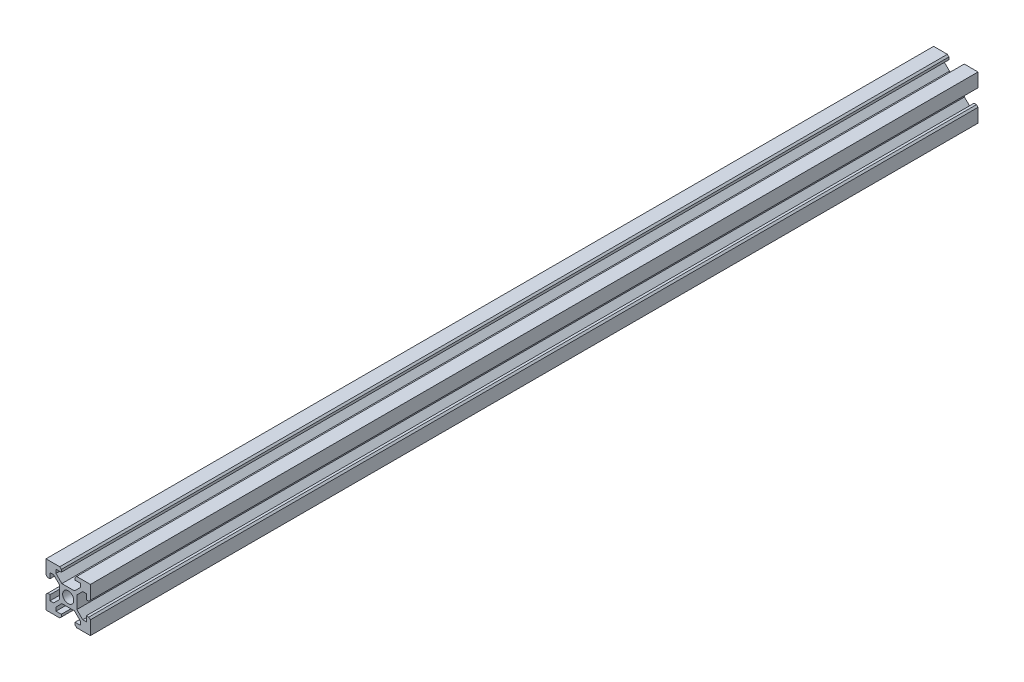
SolidWorks part; units mm, degrees
material "Cast Alloy Steel"
ref_plane "Front Plane" through (0, 0, 0) normal (0, 0, 1) x (1, 0, 0)
ref_plane "Top Plane" through (0, 0, 0) normal (0, 1, 0) x (1, 0, 0)
ref_plane "Right Plane" through (0, 0, 0) normal (1, 0, 0) x (0, 0, -1)
sketch "Sketch1" plane through (0, 0, 0) normal (0, 0, 1) x (1, 0, 0)
  line L0 (3.9, -2.8393) -> (6.5607, -5.5)
  line L1 (-10, 10) -> (10, 10) construction
  line L2 (-10, 10) -> (-10, -10) construction
  line L3 (-10, -10) -> (10, -10) construction
  line L4 (10, 10) -> (10, -10) construction
  line L5 (-10, 10) -> (10, -10) construction
  line L6 (-10, -10) -> (10, 10) construction
  line L7 (-3.9, -3.9) -> (3.9, -3.9) construction
  line L8 (-3.9, -3.9) -> (-3.9, 3.9) construction
  line L9 (-3.9, 3.9) -> (3.9, 3.9) construction
  line L10 (3.9, -3.9) -> (3.9, 3.9) construction
  line L11 (-3.9, -3.9) -> (3.9, 3.9) construction
  line L12 (-3.9, 3.9) -> (3.9, -3.9) construction
  line L13 (-10, 10) -> (-5.5, 10) construction
  line L14 (-10, 10) -> (-10, 5.5) construction
  line L15 (-10, 5.5) -> (-5.5, 5.5) construction
  line L16 (-5.5, 10) -> (-5.5, 5.5) construction
  line L17 (10, 10) -> (5.5, 10) construction
  line L18 (10, 10) -> (10, 5.5) construction
  line L19 (10, 5.5) -> (5.5, 5.5) construction
  line L20 (5.5, 10) -> (5.5, 5.5) construction
  line L21 (-10, -10) -> (-5.5, -10) construction
  line L22 (-10, -10) -> (-10, -5.5) construction
  line L23 (-10, -5.5) -> (-5.5, -5.5) construction
  line L24 (-5.5, -10) -> (-5.5, -5.5) construction
  line L25 (10, -10) -> (5.5, -10) construction
  line L26 (10, -10) -> (10, -5.5) construction
  line L27 (10, -5.5) -> (5.5, -5.5) construction
  line L28 (5.5, -10) -> (5.5, -5.5) construction
  line L29 (2.8393, -3.9) -> (5.5, -6.5607)
  line L30 (-5.5, 6.5607) -> (-2.8393, 3.9)
  line L31 (-6.5607, 5.5) -> (-3.9, 2.8393)
  line L32 (5.5, 6.5607) -> (2.8393, 3.9)
  line L33 (6.5607, 5.5) -> (3.9, 2.8393)
  line L34 (-6.5607, -5.5) -> (-3.9, -2.8393)
  line L35 (-5.5, -6.5607) -> (-2.8393, -3.9)
  line L36 (-2.8393, 3.9) -> (2.8393, 3.9)
  line L37 (-3.9, 2.8393) -> (-3.9, -2.8393)
  line L38 (-2.8393, -3.9) -> (2.8393, -3.9)
  line L39 (3.9, -2.8393) -> (3.9, 2.8393)
  line L40 (5.5, 6.5607) -> (5.5, 8.2007)
  line L41 (5.5, 8.2007) -> (3.1, 8.2007)
  line L42 (3.1, 8.2007) -> (3.1, 9.3)
  line L43 (3.1, 9.3) -> (3.8, 10)
  line L44 (3.8, 10) -> (10, 10)
  line L45 (10, 10) -> (10, 3.8)
  line L46 (10, 3.8) -> (9.3, 3.1)
  line L47 (9.3, 3.1) -> (8.2007, 3.1)
  line L48 (8.2007, 3.1) -> (8.2007, 5.5)
  line L49 (8.2007, 5.5) -> (6.5607, 5.5)
  line L50 (3.1, -8.2007) -> (5.5, -8.2007)
  line L51 (3.1, -9.3) -> (3.1, -8.2007)
  line L52 (3.8, -10) -> (3.1, -9.3)
  line L53 (10, -10) -> (3.8, -10)
  line L54 (10, -3.8) -> (10, -10)
  line L55 (9.3, -3.1) -> (10, -3.8)
  line L56 (8.2007, -3.1) -> (9.3, -3.1)
  line L57 (8.2007, -5.5) -> (8.2007, -3.1)
  line L58 (6.5607, -5.5) -> (8.2007, -5.5)
  line L59 (5.5, -8.2007) -> (5.5, -6.5607)
  line L60 (-8.2007, -3.1) -> (-8.2007, -5.5)
  line L61 (-9.3, -3.1) -> (-8.2007, -3.1)
  line L62 (-10, -3.8) -> (-9.3, -3.1)
  line L63 (-10, -10) -> (-10, -3.8)
  line L64 (-3.8, -10) -> (-10, -10)
  line L65 (-3.1, -9.3) -> (-3.8, -10)
  line L66 (-3.1, -8.2007) -> (-3.1, -9.3)
  line L67 (-5.5, -8.2007) -> (-3.1, -8.2007)
  line L68 (-5.5, -6.5607) -> (-5.5, -8.2007)
  line L69 (-8.2007, -5.5) -> (-6.5607, -5.5)
  line L70 (-3.1, 8.2007) -> (-5.5, 8.2007)
  line L71 (-3.1, 9.3) -> (-3.1, 8.2007)
  line L72 (-3.8, 10) -> (-3.1, 9.3)
  line L73 (-10, 10) -> (-3.8, 10)
  line L74 (-10, 3.8) -> (-10, 10)
  line L75 (-9.3, 3.1) -> (-10, 3.8)
  line L76 (-8.2007, 3.1) -> (-9.3, 3.1)
  line L77 (-8.2007, 5.5) -> (-8.2007, 3.1)
  line L78 (-6.5607, 5.5) -> (-8.2007, 5.5)
  line L79 (-5.5, 8.2007) -> (-5.5, 6.5607)
  circle A0 centre (0, 0) radius 2.5
  point P83 (0, 0)
  dimension "D1" = 5
  dimension "D2" = 20
  dimension "D3" = 7.8
  dimension "D4" = 4.5
  dimension "D5" = 1.5
  dimension "D6" = 0.75
  dimension "D7" = 1.5
  dimension "D8" = 0.75
  dimension "D9" = 1.5
  dimension "D10" = 0.75
  dimension "D11" = 1.5
  dimension "D12" = 0.75
  dimension "D13" = 1.64
  dimension "D14" = 45
  dimension "D15" = 3.1
  dimension "D16" = 6.2
  dimension "D17" = 6.2
  dimension "D18" = 3.1
  dimension "D19" = 4
extrude "Boss-Extrude1" add sketch "Sketch1" along normal mid plane 400 contours L79 L70 L71 L72 L73 L74 L75 L76 L77 L78 L31 L37 L34 L69 L60 L61 L62 L63 L64 L65 L66 L67 L68 L35 L38 L29 L59 L50 L51 L52 L53 L54 L55 L56 L57 L58 L0 L39 L33 L49 L48 L47 L46 L45 L44 L43 L42 L41 L40 L32 L36
